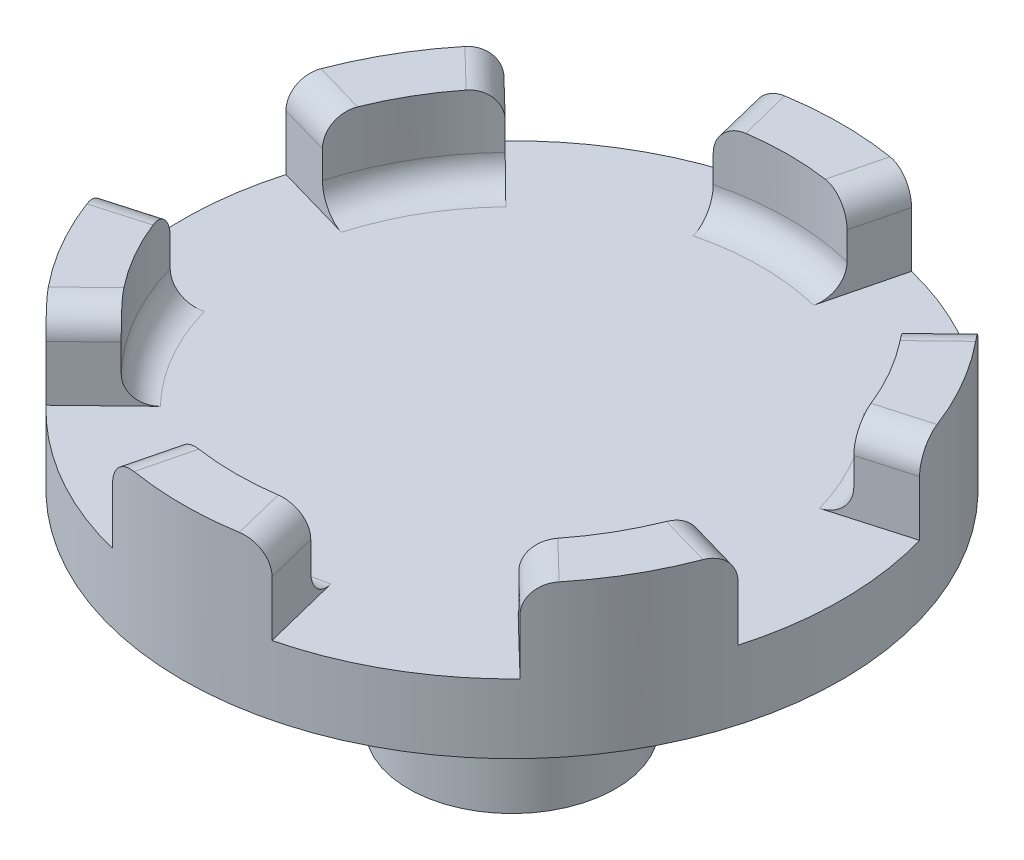
SolidWorks part; units mm, degrees
ref_plane "Front Plane" through (0, 0, 0) normal (0, 0, 1) x (1, 0, 0)
ref_plane "Top Plane" through (0, 0, 0) normal (0, 1, 0) x (1, 0, 0)
ref_plane "Right Plane" through (0, 0, 0) normal (1, 0, 0) x (0, 0, -1)
sketch "Sketch1" plane through (0, 0, 0) normal (0, 1, 0) x (1, 0, 0)
  circle A0 centre (0, 0) radius 30.2895
  dimension "D1" = 60.579
extrude "Boss-Extrude1" add sketch "Sketch1" along normal blind 6.35
sketch "Sketch2" plane through (0, 6.35, 0) normal (0, 1, 0) x (1, 0, 0)
  line L0 (-6.1482, -24.6447) -> (-7.3317, -29.3888)
  line L1 (-20.3643, -26.1375) -> (5.7009, -32.64) construction
  line L2 (-16.2324, -22.129) -> (3.936, -27.1604) construction
  line L3 (6.1482, -24.6447) -> (7.3317, -29.3888)
  line L4 (4.3414, -25.0954) -> (7.9549, -24.194) construction
  line L5 (8.1027, -29.1964) -> (6.5606, -29.5811) construction
  line L6 (-6.1482, -24.6447) -> (6.1482, -24.6447) construction
  line L7 (0, 0) -> (0, -49.2894) construction
  line L8 (-37.5524, 0) -> (37.5524, 0) construction
  line L9 (-24.417, -6.9979) -> (-29.1173, -8.345)
  line L10 (-18.2688, -17.6468) -> (-21.7856, -21.0438)
  line L11 (-18.2688, 17.6468) -> (-21.7856, 21.0438)
  line L12 (-24.417, 6.9979) -> (-29.1173, 8.345)
  line L13 (6.1482, 24.6447) -> (7.3317, 29.3888)
  line L14 (-6.1482, 24.6447) -> (-7.3317, 29.3888)
  line L15 (24.417, 6.9979) -> (29.1173, 8.345)
  line L16 (18.2688, 17.6468) -> (21.7856, 21.0438)
  line L17 (18.2688, -17.6468) -> (21.7856, -21.0438)
  line L18 (24.417, -6.9979) -> (29.1173, -8.345)
  line L19 (0, 0) -> (-6.1482, -24.6447) construction
  line L20 (0, 0) -> (-24.417, -6.9979) construction
  circle A0 centre (0, 0) radius 25.4 construction
  arc A1 (-18.2688, -17.6468) -> (-24.417, -6.9979) centre (0, 0) cw
  arc A2 (-21.7856, -21.0438) -> (-29.1173, -8.345) centre (0, 0) cw
  circle A3 centre (0, 0) radius 30.2895 construction
  arc A4 (6.1482, -24.6447) -> (-6.1482, -24.6447) centre (0, 0) cw
  arc A5 (7.3317, -29.3888) -> (-7.3317, -29.3888) centre (0, 0) cw
  arc A6 (-24.417, 6.9979) -> (-18.2688, 17.6468) centre (0, 0) cw
  arc A7 (-29.1173, 8.345) -> (-21.7856, 21.0438) centre (0, 0) cw
  arc A8 (-6.1482, 24.6447) -> (6.1482, 24.6447) centre (0, 0) cw
  arc A9 (-7.3317, 29.3888) -> (7.3317, 29.3888) centre (0, 0) cw
  arc A10 (18.2688, 17.6468) -> (24.417, 6.9979) centre (0, 0) cw
  arc A11 (21.7856, 21.0438) -> (29.1173, 8.345) centre (0, 0) cw
  arc A12 (24.417, -6.9979) -> (18.2688, -17.6468) centre (0, 0) cw
  arc A13 (29.1173, -8.345) -> (21.7856, -21.0438) centre (0, 0) cw
  point P10 (-7.3317, -29.3888)
  point P13 (-6.1482, -24.6447)
  point P18 (6.1482, -24.6447)
  point P20 (7.3317, -29.3888)
  point P23 (0, -24.6447)
  point P28 (0, 0)
  circle M16 centre (0, 0) radius 30.2895
  dimension "D1" = 50.8
  dimension "D2" = 6
  dimension "D3" = 60
extrude "Boss-Extrude2" add sketch "Sketch2" along normal blind 7.62 contours L3 A4 L0 M16 | L18 A12 L17 M16 | L16 A10 L15 M16 | L12 A6 L11 M16 | L10 A1 L9 M16 | A9 L13 A8 L14
fillet "Fillet1" radius 2.54 12 edges at (26.7671, 13.97, 7.6714) (26.7671, 13.97, -7.6714) (20.0272, 13.97, -19.3453) (6.7399, 13.97, -27.0167) (-6.7399, 13.97, -27.0167) (-20.0272, 13.97, -19.3453) (-26.7671, 13.97, -7.6714) (-26.7671, 13.97, 7.6714) (-20.0272, 13.97, 19.3453) (-6.7399, 13.97, 27.0167) (20.0272, 13.97, 19.3453) (6.7399, 13.97, 27.0167)
sketch "Sketch3" plane through (0, 0, 0) normal (0, -1, 0) x (1, 0, 0)
  circle A0 centre (0, 0) radius 12.7
  dimension "D1" = 25.4
extrude "Boss-Extrude3" add sketch "Sketch3" along normal blind 6.35
fillet "Fillet2" radius 2.54 6 edges at (-21.997, 6.35, 12.7) (-21.997, 6.35, -12.7) (0, 6.35, -25.4) (21.997, 6.35, -12.7) (0, 6.35, 25.4) (21.997, 6.35, 12.7)
sketch "Sketch4" plane through (0, -6.35, 0) normal (0, -1, 0) x (1, 0, 0)
  circle A0 centre (0, 0) radius 9.525
  dimension "D1" = 19.05
extrude "Boss-Extrude4" add sketch "Sketch4" along normal blind 12.7
